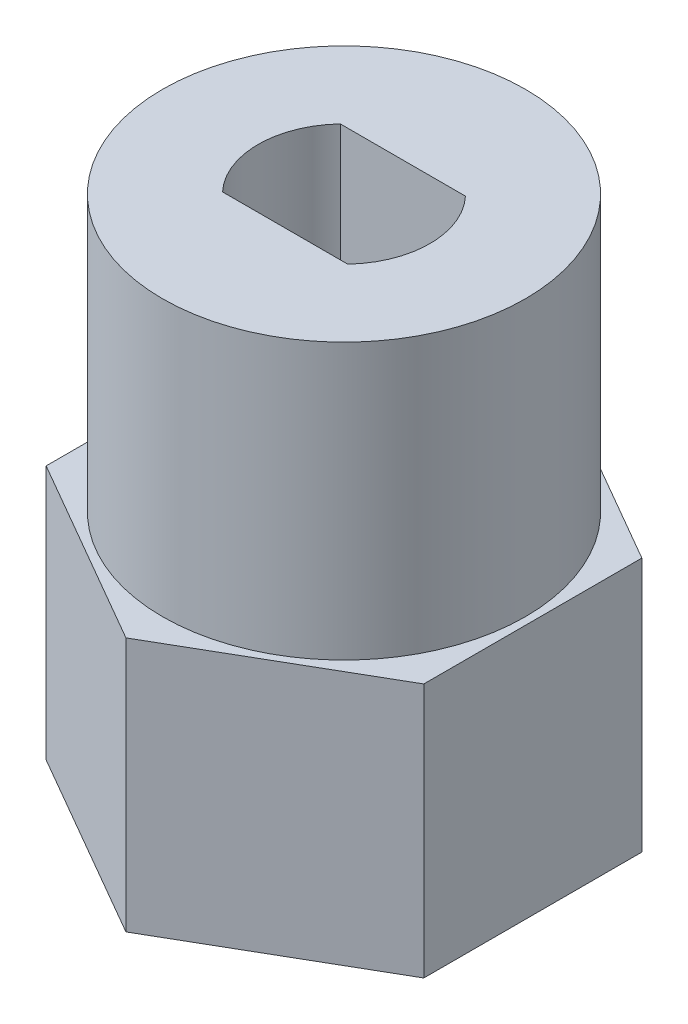
SolidWorks part; units mm, degrees
material "黄铜"
ref_plane "前视基准面" through (0, 0, 0) normal (0, 0, 1) x (1, 0, 0)
ref_plane "上视基准面" through (0, 0, 0) normal (0, 1, 0) x (1, 0, 0)
ref_plane "右视基准面" through (0, 0, 0) normal (1, 0, 0) x (0, 0, -1)
sketch "草图1" plane through (0, 0, 0) normal (0, 1, 0) x (1, 0, 0)
  line L1 (0, 6.85) -> (-5.9323, 3.425)
  line L2 (-5.9323, 3.425) -> (-5.9323, -3.425)
  line L3 (-5.9323, -3.425) -> (0, -6.85)
  line L4 (0, -6.85) -> (5.9323, -3.425)
  line L5 (5.9323, -3.425) -> (5.9323, 3.425)
  line L6 (5.9323, 3.425) -> (0, 6.85)
  circle A0 centre (0, 0) radius 5.9323 construction
  circle A1 centre (0, 0) radius 1.6
  dimension "D2" = 3.2
  dimension "D1" = 13.7
extrude "凸台-拉伸1" add sketch "草图1" along normal blind 8
cosmetic thread "装饰螺纹线1" parameters "D2"=4
sketch "草图2" plane through (0, 8, 0) normal (0, 1, 0) x (1, 0, 0)
  line L0 (-2.7, 0) -> (2.7, 0) construction
  line L1 (-1.9666, 1.85) -> (1.9666, 1.85)
  line L2 (-1.9666, -1.85) -> (1.9666, -1.85)
  circle A1 centre (0, 0) radius 5.7
  arc A2 (-1.9666, 1.85) -> (-1.9666, -1.85) centre (0, 0) ccw
  arc A3 (1.9666, 1.85) -> (1.9666, -1.85) centre (0, 0) cw
  dimension "D2" = 11.4
  dimension "D3" = 3.7
extrude "凸台-拉伸2" add sketch "草图2" along normal blind 8.65
